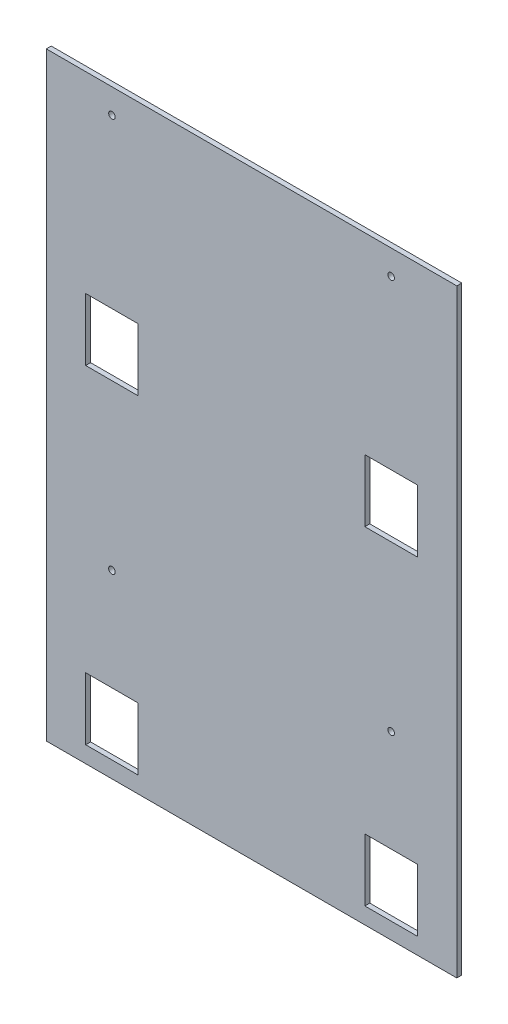
SolidWorks part; units mm, degrees
ref_plane "Front Plane" through (0, 0, 0) normal (0, 0, 1) x (1, 0, 0)
ref_plane "Top Plane" through (0, 0, 0) normal (0, 1, 0) x (1, 0, 0)
ref_plane "Right Plane" through (0, 0, 0) normal (1, 0, 0) x (0, 0, -1)
sketch "Sketch1" plane through (0, 0, 0) normal (0, 0, 1) x (1, 0, 0)
  line L1 (125, -182.5) -> (-125, -182.5)
  line L2 (125, -182.5) -> (125, 182.5)
  line L3 (125, 182.5) -> (-125, 182.5)
  line L4 (-125, -182.5) -> (-125, 182.5)
  line L5 (125, -182.5) -> (-125, 182.5) construction
  line L6 (125, 182.5) -> (-125, -182.5) construction
  point P0 (0, 0)
  dimension "D1" = 250
  dimension "D2" = 365
extrude "Boss-Extrude1" add sketch "Sketch1" along normal blind 3
sketch "Sketch3" plane through (0, 0, 3) normal (0, 0, 1) x (1, 0, 0)
  line L0 (-125, 182.5) -> (-125, -182.5) construction
  line L1 (125, 182.5) -> (-125, 182.5) construction
  line L2 (0, -55) -> (0, 55) construction
  circle A0 centre (-85, 167.5) radius 2
  circle A1 centre (-85, 47.5) radius 2
  circle A2 centre (-85, -72.5) radius 2
  circle A3 centre (-85, -192.5) radius 2
  circle A4 centre (85, -192.5) radius 2
  circle A5 centre (85, -72.5) radius 2
  circle A6 centre (85, 47.5) radius 2
  circle A7 centre (85, 167.5) radius 2
  dimension "D1" = 40
  dimension "D2" = 15
extrude "Cut-Extrude2" cut sketch "Sketch3" against normal blind 3
sketch "Sketch4" plane through (0, 0, 0) normal (0, 0, -1) x (-1, 0, 0)
  line L0 (-97, -135.5) -> (-73, -135.5) construction
  line L1 (-101, -134.5) -> (-69, -134.5)
  line L2 (-101, -134.5) -> (-101, -172.5)
  line L3 (-101, -172.5) -> (-69, -172.5)
  line L4 (-69, -134.5) -> (-69, -172.5)
  line L5 (-70, -164.5) -> (-70, -142.5) construction
  line L6 (-100, -164.5) -> (-100, -142.5) construction
  line L7 (-97, -171.5) -> (-73, -171.5) construction
  line L8 (0, 1.65) -> (0, -1.65) construction
  line L9 (69, -134.5) -> (69, -172.5)
  line L10 (101, -172.5) -> (69, -172.5)
  line L11 (101, -134.5) -> (101, -172.5)
  line L12 (101, -134.5) -> (69, -134.5)
  line L13 (-101, 65.5) -> (-69, 65.5)
  line L14 (-101, 65.5) -> (-101, 27.5)
  line L15 (-101, 27.5) -> (-69, 27.5)
  line L16 (-69, 65.5) -> (-69, 27.5)
  line L17 (69, 65.5) -> (69, 27.5)
  line L18 (101, 27.5) -> (69, 27.5)
  line L19 (101, 65.5) -> (101, 27.5)
  line L20 (101, 65.5) -> (69, 65.5)
  dimension "D1" = 1
  dimension "D2" = 1
  dimension "D3" = 1
  dimension "D4" = 1
  dimension "D5" = 2
extrude "Cut-Extrude3" cut sketch "Sketch4" against normal blind 10
